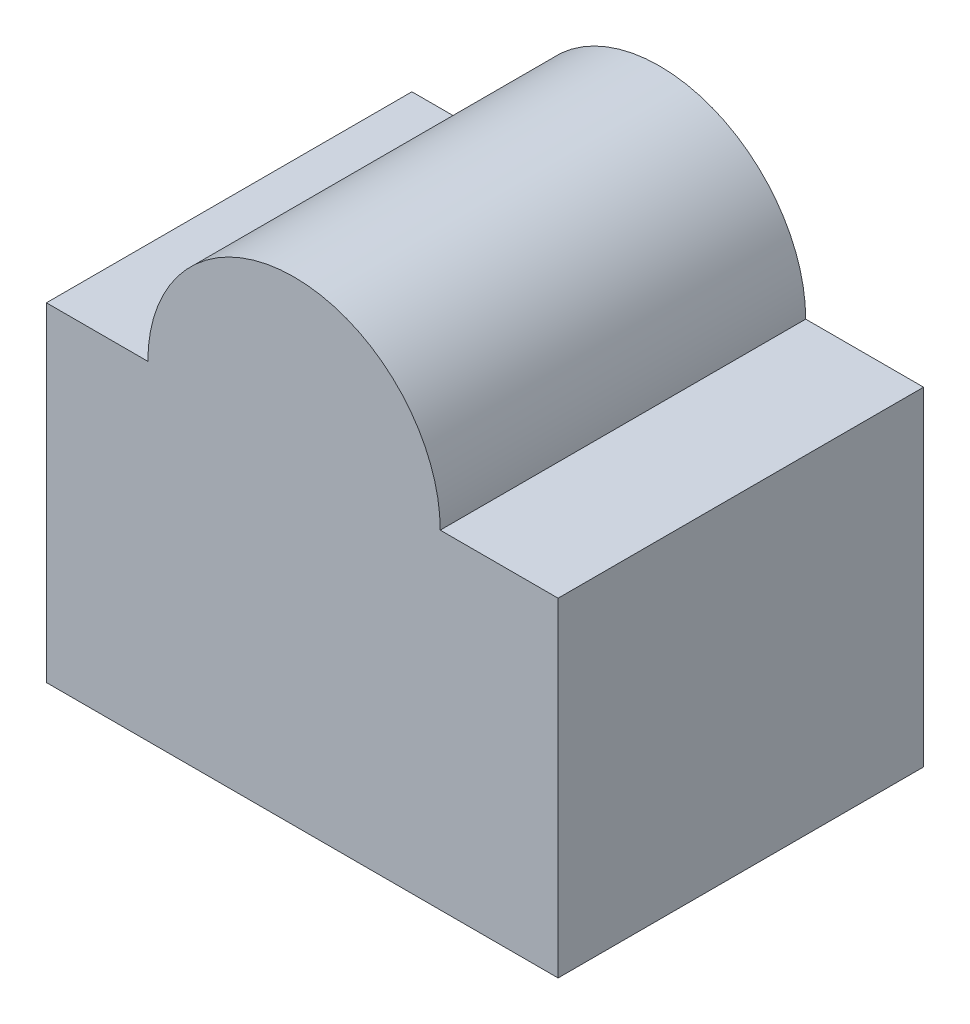
SolidWorks part; units mm, degrees
ref_plane "Plan de face" through (0, 0, 0) normal (0, 0, 1) x (1, 0, 0)
ref_plane "Plan de dessus" through (0, 0, 0) normal (0, 1, 0) x (1, 0, 0)
ref_plane "Plan de droite" through (0, 0, 0) normal (1, 0, 0) x (0, 0, -1)
sketch "Esquisse1" plane through (0, 0, 0) normal (0, 0, 1) x (1, 0, 0)
  line L0 (0, 0) -> (700, 0)
  line L1 (700, 0) -> (700, 450)
  line L2 (700, 450) -> (538.7581, 450)
  line L3 (0, 0) -> (0, 450)
  line L4 (0, 450) -> (138.7581, 450)
  arc A0 (538.7581, 450) -> (138.7581, 450) centre (338.7581, 450) ccw
  dimension "D3" = 200
  dimension "D1" = 700
  dimension "D2" = 450
extrude "Boss.-Extru.1" add sketch "Esquisse1" along normal blind 500
